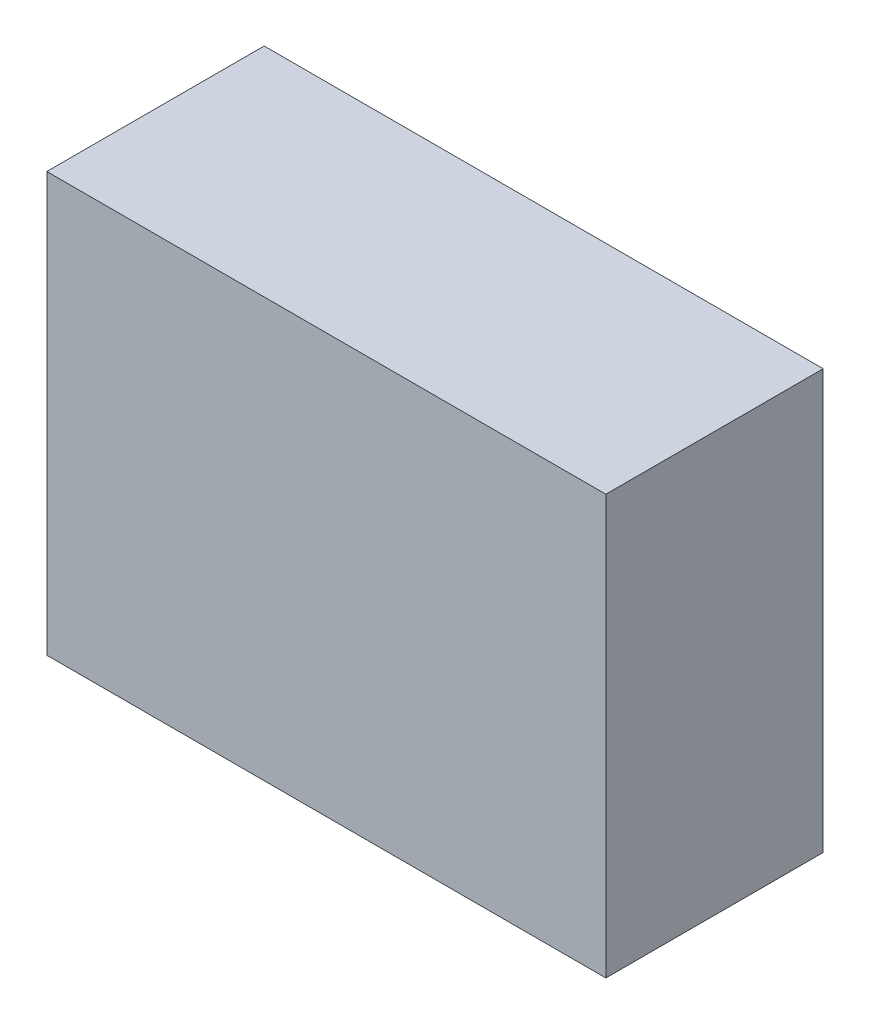
SolidWorks part; units mm, degrees
ref_plane "Front Plane" through (0, 0, 0) normal (0, 0, 1) x (1, 0, 0)
ref_plane "Top Plane" through (0, 0, 0) normal (0, 1, 0) x (1, 0, 0)
ref_plane "Right Plane" through (0, 0, 0) normal (1, 0, 0) x (0, 0, -1)
sketch "Sketch1" plane through (0, 0, 0) normal (0, 0, 1) x (1, 0, 0)
  line L1 (-23.15, -17.35) -> (23.15, -17.35)
  line L2 (-23.15, -17.35) -> (-23.15, 17.35)
  line L3 (-23.15, 17.35) -> (23.15, 17.35)
  line L4 (23.15, -17.35) -> (23.15, 17.35)
  line L5 (-23.15, -17.35) -> (23.15, 17.35) construction
  line L6 (-23.15, 17.35) -> (23.15, -17.35) construction
  point P0 (0, 0)
extrude "Envelope" add sketch "Sketch1" along normal blind 18
